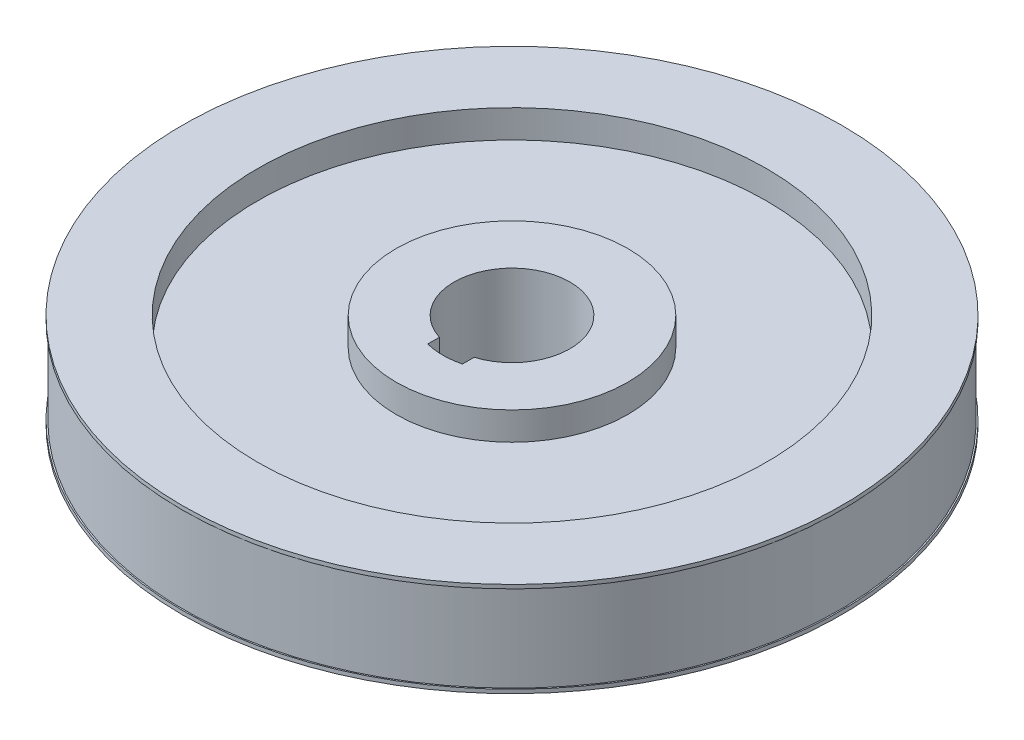
SolidWorks part; units mm, degrees
ref_plane "Front Plane" through (0, 0, 0) normal (0, 0, 1) x (1, 0, 0)
ref_plane "Top Plane" through (0, 0, 0) normal (0, 1, 0) x (1, 0, 0)
ref_plane "Right Plane" through (0, 0, 0) normal (1, 0, 0) x (0, 0, -1)
sketch "Sketch1" plane through (0, 0, 0) normal (0, 1, 0) x (1, 0, 0)
  circle A0 centre (0, 0) radius 170
  dimension "D1" = 340
extrude "Boss-Extrude1" add sketch "Sketch1" along normal mid plane 45
sketch "Sketch2" plane through (0, 22.5, 0) normal (0, 1, 0) x (1, 0, 0)
  circle A2 centre (0, 0) radius 170.69
  circle A3 centre (0, 0) radius 170.69
  dimension "D1" = 0.69
extrude "Boss-Extrude2" add sketch "Sketch2" along normal blind 2
mirror "Mirror1" about plane through (0, 0, 0) normal (0, 1, 0) of "Boss-Extrude2"
sketch "Sketch3" plane through (0, 0, 0) normal (0, 1, 0) x (1, 0, 0)
  circle A0 centre (0, 0) radius 131.78
  circle A1 centre (0, 0) radius 60
  circle A2 centre (0, 0) radius 170.69 construction
  dimension "D1" = 120
  dimension "D2" = 38.91
extrude "Cut-Extrude1" cut sketch "Sketch3" against normal through all from offset 10 offset against normal yes
mirror "Mirror3" about plane through (0, 0, 0) normal (0, 1, 0) of "Cut-Extrude1"
sketch "Sketch4" plane through (0, -24.5, 0) normal (0, -1, 0) x (1, 0, 0)
  circle A0 centre (0, 0) radius 30
  dimension "D1" = 60
extrude "Cut-Extrude2" cut sketch "Sketch4" against normal through all
sketch "Sketch5" plane through (0, -24.5, 0) normal (0, -1, 0) x (1, 0, 0)
  line L0 (0, 18.0698) -> (0, 35.8) construction
  line L1 (-9, 34.6503) -> (-9, 18.0698)
  line L2 (9, 34.6503) -> (9, 18.0698)
  line L3 (-9, 18.0698) -> (9, 18.0698)
  circle A2 centre (0, 0) radius 35.8
  arc A3 (9, 34.6503) -> (-9, 34.6503) centre (0, 0) ccw
  dimension "D1" = 9
  dimension "D2" = 5.8
extrude "Cut-Extrude3" cut sketch "Sketch5" against normal through all
